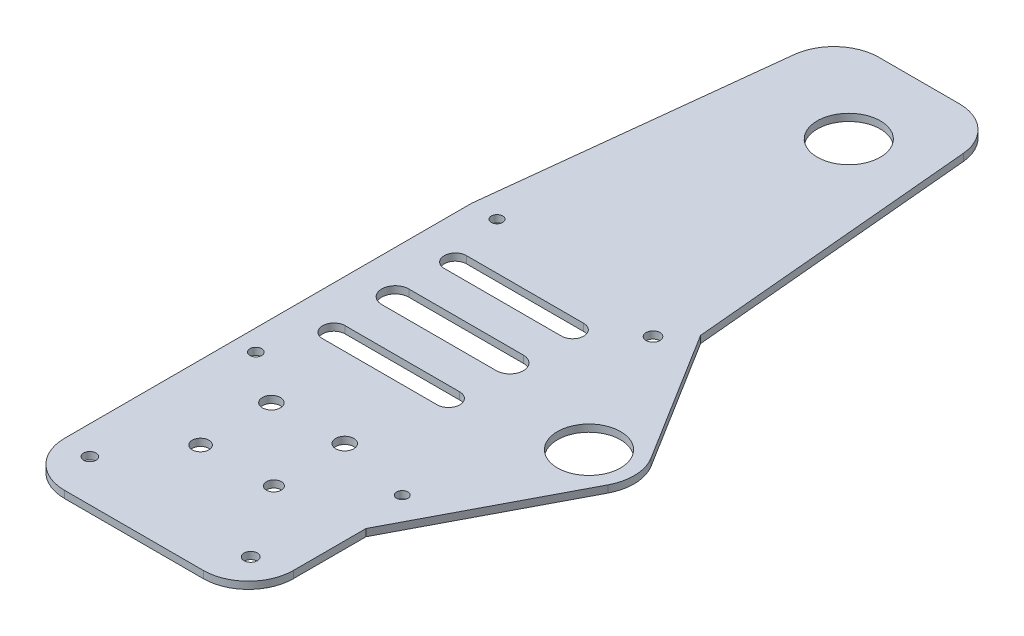
SolidWorks part; units mm, degrees
ref_plane "Front" through (0, 0, 0) normal (0, 0, 1) x (1, 0, 0)
ref_plane "Top" through (0, 0, 0) normal (0, 1, 0) x (1, 0, 0)
ref_plane "Right" through (0, 0, 0) normal (1, 0, 0) x (0, 0, -1)
sketch "Sketch1" plane through (0, 0, 0) normal (0, 1, 0) x (1, 0, 0)
  line L0 (10.4543, 228.6) -> (0, 135.3627)
  line L1 (0, 0) -> (50.8, 0)
  line L2 (0, 0) -> (0, 228.6)
  line L3 (0, 228.6) -> (50.8, 228.6)
  line L4 (50.8, 0) -> (50.8, 228.6)
  line L5 (42.3273, 228.6) -> (50.8, 135.3627)
  line L8 (50.8, 0) -> (24.327, 0)
  line L16 (50.8, 120.6192) -> (50.8, 104.4882)
  line L18 (50.8, 64.8791) -> (50.8, 87.4235)
  line L20 (9.492, 92.7849) -> (34.9257, 92.7849)
  line L21 (9.492, 92.7849) -> (9.492, 97.7849)
  line L22 (9.492, 97.7849) -> (34.9257, 97.7849)
  line L23 (34.9257, 92.7849) -> (34.9257, 97.7849)
  line L25 (9.492, 105.9099) -> (34.9257, 105.9099)
  line L26 (9.492, 105.9099) -> (9.492, 111.9099)
  line L27 (9.492, 111.9099) -> (34.9257, 111.9099)
  line L28 (34.9257, 105.9099) -> (34.9257, 111.9099)
  line L30 (9.492, 119.7849) -> (35.5097, 119.7849)
  line L31 (9.492, 119.7849) -> (9.492, 124.7158)
  line L32 (9.492, 124.7158) -> (35.5097, 124.7158)
  line L33 (35.5097, 119.7849) -> (35.5097, 124.7158)
  circle A12 centre (60.4, 101.001) radius 10
  circle A13 centre (29.5042, 189.5572) radius 7
  circle A22 centre (9.492, 95.2849) radius 2.5
  circle A23 centre (34.9257, 95.2849) radius 2.5
  circle A24 centre (34.9257, 108.9099) radius 3
  circle A25 centre (9.492, 108.9099) radius 3
  circle A26 centre (9.492, 122.2504) radius 2.4654
  circle A27 centre (35.5097, 122.2504) radius 2.4654
  circle A32 centre (43.4477, 42.8684) radius 1.4834
  circle A33 centre (6.3356, 44.2888) radius 1.3882
  circle A34 centre (4.6595, 82.7932) radius 1.3149
  circle A35 centre (48.401, 71.551) radius 1.2486
  circle A36 centre (45.7477, 129.8635) radius 1.5391
  circle A37 centre (5.8847, 135.1031) radius 1.2556
  circle A38 centre (16.3891, 58.8042) radius 1.8564
  circle A39 centre (32.3868, 59.0801) radius 1.65
  circle A40 centre (32.1109, 75.0777) radius 2
  circle A41 centre (16.1132, 74.8019) radius 2
  dimension "D3" = 20
  dimension "D4" = 103.8842
  dimension "D6" = 14
  dimension "D7" = 116.6901
  dimension "D1" = 50.8
  dimension "D2" = 228.6
  dimension "D8" = 130.8151
extrude "Boss-Extrude1" add sketch "Sketch1" along normal blind 1.5875 contours L1 L4 L3 L0 L2
sketch "Sketch4" plane through (0, 0, -228.6) normal (0, 0, -1) x (-1, 0, 0)
  line L1 (-61.3109, 11.9192) -> (4.9615, 11.9192)
  line L2 (-61.3109, 11.9192) -> (-61.3109, -15.8811)
  line L3 (-61.3109, -15.8811) -> (4.9615, -15.8811)
  line L4 (4.9615, 11.9192) -> (4.9615, -15.8811)
extrude "Cut-Extrude2" cut sketch "Sketch4" against normal blind 20
fillet "Fillet3" radius 10 1 edges at (44.1447, 0.7937, -208.6)
fillet "Fillet4" radius 10 3 edges at (50.8, 0.7937, 0) (0, 0.7937, 0) (8.2118, 0.7937, -208.6)
sketch "Sketch6" plane through (0, 1.5875, 0) normal (0, 1, 0) x (1, 0, 0)
  line L0 (68.8909, 106.2834) -> (50.8, 135.3627)
  line L1 (50.8, 135.3627) -> (50.8, 103.801)
  line L2 (69.2582, 96.3607) -> (50.8, 61.1242)
  line L3 (50.8, 10) -> (50.8, 98.201) construction
  line L4 (50.8, 61.1242) -> (50.8, 96.3607)
  line L5 (50.8, 96.3607) -> (50.8, 98.201)
  circle A0 centre (60.4, 101.001) radius 10
extrude "Boss-Extrude3" add sketch "Sketch6" against normal blind 1.5875
sketch "Sketch7" plane through (0, 1.5875, 0) normal (0, 1, 0) x (1, 0, 0)
  circle A0 centre (60.4, 101.001) radius 7
  dimension "D1" = 14
extrude "Cut-Extrude3" cut sketch "Sketch7" against normal blind 1.5875
sketch "Sketch8" plane through (0, 0, 0) normal (0, 0, 1) x (1, 0, 0)
  line L1 (-21.5979, 31.8127) -> (78.5082, 31.8127)
  line L2 (-21.5979, 31.8127) -> (-21.5979, -28.4046)
  line L3 (-21.5979, -28.4046) -> (78.5082, -28.4046)
  line L4 (78.5082, 31.8127) -> (78.5082, -28.4046)
extrude "Cut-Extrude4" cut sketch "Sketch8" against normal blind 35
fillet "Fillet5" radius 10 2 edges at (0, 0.7937, -35) (50.8, 0.7937, -35)
equation "\"7i\"=101.6"
